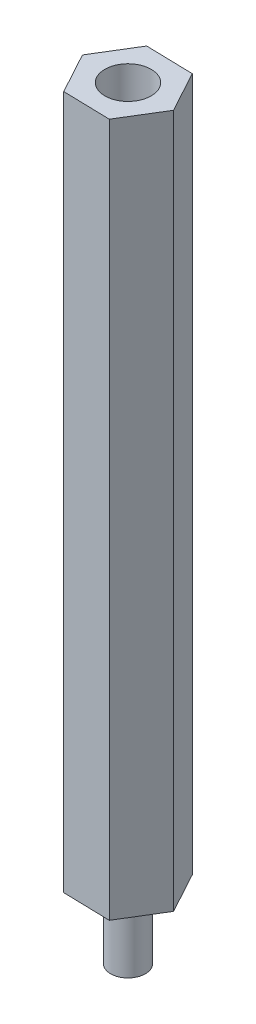
SolidWorks part; units mm, degrees
ref_plane "정면" through (0, 0, 0) normal (0, 0, 1) x (1, 0, 0)
ref_plane "윗면" through (0, 0, 0) normal (0, 1, 0) x (1, 0, 0)
ref_plane "우측면" through (0, 0, 0) normal (1, 0, 0) x (0, 0, -1)
sketch "스케치1" plane through (0, 0, 0) normal (0, 1, 0) x (1, 0, 0)
  line L1 (1.9316, -3.55) -> (4.0402, -0.1022)
  line L2 (4.0402, -0.1022) -> (2.1086, 3.4478)
  line L3 (2.1086, 3.4478) -> (-1.9316, 3.55)
  line L4 (-1.9316, 3.55) -> (-4.0402, 0.1022)
  line L5 (-4.0402, 0.1022) -> (-2.1086, -3.4478)
  line L6 (-2.1086, -3.4478) -> (1.9316, -3.55)
  circle A0 centre (0, 0) radius 3.5 construction
  dimension "D1" = 7
extrude "보스-돌출1" add sketch "스케치1" along normal blind 60
sketch "스케치2" plane through (0, 60, 0) normal (0, 1, 0) x (1, 0, 0)
  circle A0 centre (0, 0) radius 2
  dimension "D1" = 4
extrude "컷-돌출1" cut sketch "스케치2" against normal blind 8
sketch "스케치3" plane through (0, 0, 0) normal (0, -1, 0) x (1, 0, 0)
  circle A0 centre (0, 0) radius 1.5
  dimension "D1" = 3
extrude "보스-돌출2" add sketch "스케치3" along normal blind 6
